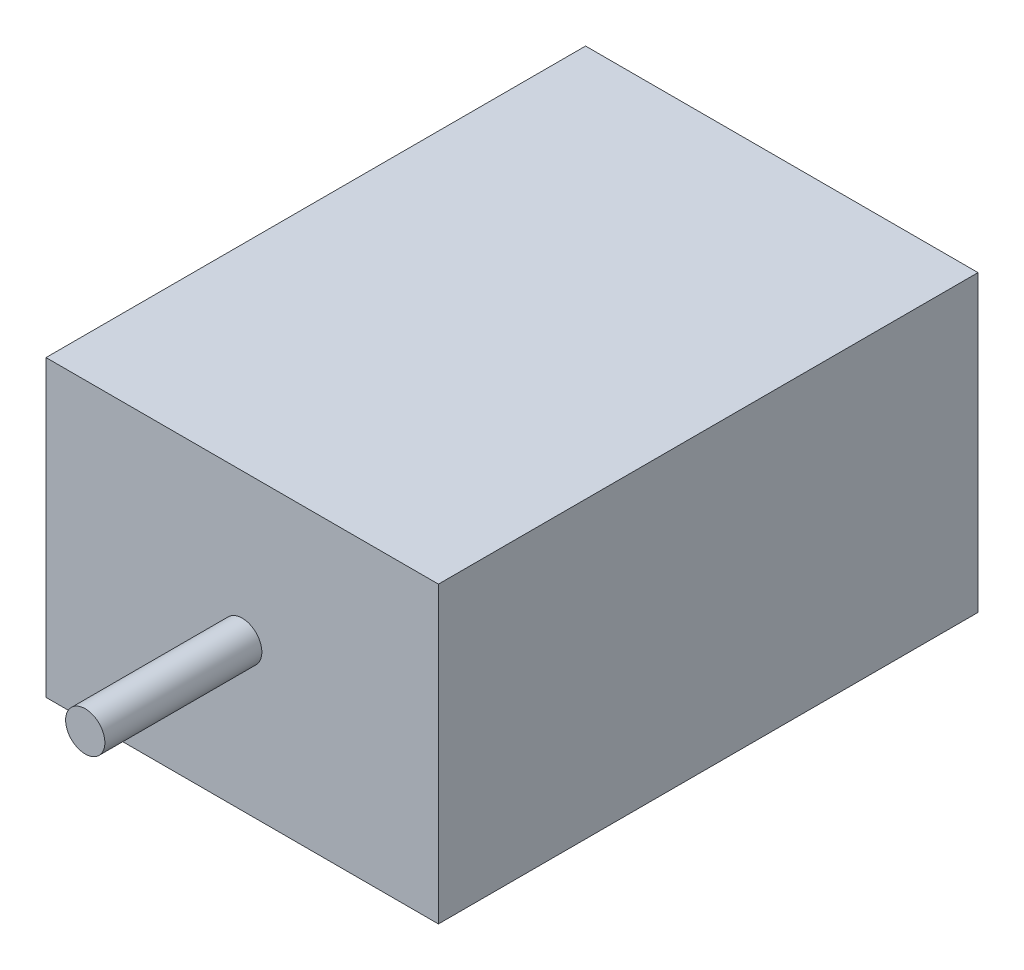
SolidWorks part; units mm, degrees
ref_plane "Front Plane" through (0, 0, 0) normal (0, 0, 1) x (1, 0, 0)
ref_plane "Top Plane" through (0, 0, 0) normal (0, 1, 0) x (1, 0, 0)
ref_plane "Right Plane" through (0, 0, 0) normal (1, 0, 0) x (0, 0, -1)
sketch "Sketch1" plane through (0, 0, 0) normal (0, 0, 1) x (1, 0, 0)
  line L1 (-10, -7.5) -> (10, -7.5)
  line L2 (-10, -7.5) -> (-10, 7.5)
  line L3 (-10, 7.5) -> (10, 7.5)
  line L4 (10, -7.5) -> (10, 7.5)
extrude "Motor_Body_Envelope" add sketch "Sketch1" along normal blind 27.5 from offset 0
sketch "Sketch2" plane through (0, 0, 0) normal (0, 0, 1) x (1, 0, 0)
  circle A0 centre (0, 0) radius 1
extrude "Reference_2mm_Shaft" add sketch "Sketch2" along normal blind 8 from offset 27.5
